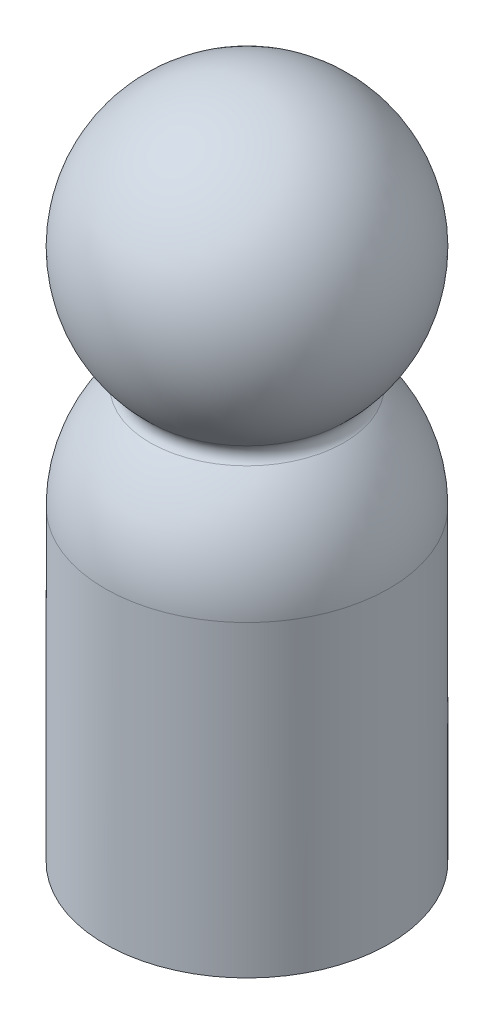
SolidWorks part; units mm, degrees
ref_plane "Front Plane" through (0, 0, 0) normal (0, 0, 1) x (1, 0, 0)
ref_plane "Top Plane" through (0, 0, 0) normal (0, 1, 0) x (1, 0, 0)
ref_plane "Right Plane" through (0, 0, 0) normal (1, 0, 0) x (0, 0, -1)
sketch "Sketch1" plane through (0, 0, 0) normal (0, 1, 0) x (1, 0, 0)
  circle A0 centre (0, 0) radius 12
extrude "Boss-Extrude1" add sketch "Sketch1" along normal blind 26
sketch "Sketch2" plane through (0, 0, 0) normal (0, 0, 1) x (1, 0, 0)
  line L0 (12, 26) -> (-12, 26) construction
  line L1 (0, 55.9438) -> (0, 26)
  line L2 (0, 26) -> (12, 26)
  line L3 (0, 55.9438) -> (0, 57)
  arc A0 (12, 26) -> (7.3314, 35.5) centre (0, 26) ccw
  arc A1 (7.3314, 35.5) -> (0, 57) centre (0, 45) ccw
  dimension "D1" = 19
  dimension "D2" = 12
revolve "Revolve1" add sketch "Sketch2" angle 360 about L1
fillet "Fillet1" radius 1 1 edges at (-7.3314, 35.5, 0)
